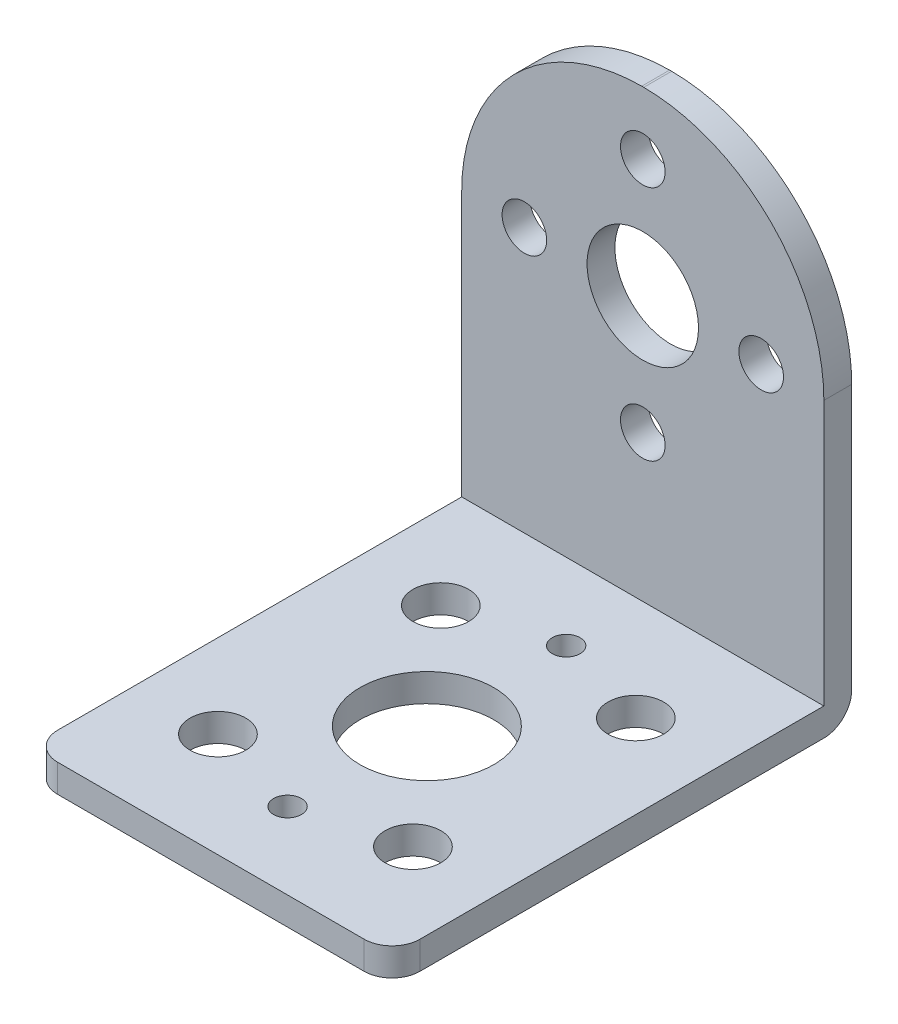
SolidWorks part; units mm, degrees
ref_plane "Front Plane" through (0, 0, 0) normal (0, 0, 1) x (1, 0, 0)
ref_plane "Top Plane" through (0, 0, 0) normal (0, 1, 0) x (1, 0, 0)
ref_plane "Right Plane" through (0, 0, 0) normal (1, 0, 0) x (0, 0, -1)
ref_plane "Plane1"
sketch "Sketch1" plane through (0, 0, 0) normal (0, 1, 0) x (-1, 0, 0)
  line L0 (-13, -15.5) -> (13, -15.5)
  line L1 (13, -15.5) -> (13, 15.5)
  line L2 (13, 15.5) -> (-13, 15.5)
  line L3 (-13, 15.5) -> (-13, -15.5)
  circle A0 centre (0, -10) radius 1
  circle A1 centre (0, 10) radius 1
  circle A2 centre (-7, 8) radius 2
  circle A3 centre (-7, -8) radius 2
  circle A4 centre (7, -8) radius 2
  circle A5 centre (7, 8) radius 2
  circle A6 centre (0, 0) radius 4.8
  dimension "D3" = 9.6
  dimension "D7" = 4
  dimension "D8" = 2
  dimension "D1" = 26
  dimension "D2" = 31
  dimension "D4" = 7.5
  dimension "D5" = 14
  dimension "D6" = 16
  dimension "D9" = 10
extrude "Extrusion1" add sketch "Sketch1" along normal blind 2 contours L2 L3 L0 L1 A6 A5 A4 A3 A2 A1 A0
ref_plane "Plane2"
sketch "Sketch2" plane through (0, 0, 0) normal (0, 1, 0) x (-1, 0, 0)
  line L0 (-13, -17.5) -> (13, -17.5)
  line L1 (13, -17.5) -> (13, -15.5)
  line L2 (13, -15.5) -> (-13, -15.5)
  line L3 (-13, -15.5) -> (-13, -17.5)
  dimension "D1" = 26
  dimension "D2" = 40.4599
  dimension "D3" = 2
  dimension "D4" = 26
extrude "Extrusion2" add sketch "Sketch2" along normal blind 34
sketch "Sketch3" plane through (0, 0, -15.5) normal (0, 0, 1) x (1, 0, 0)
  line L0 (-0.0721, 34) -> (-13, 34)
  line L1 (-13, 34) -> (-13, 21)
  line L2 (13, 21) -> (13, 34)
  line L3 (13, 34) -> (0.0721, 34)
  arc A0 (-0.0721, 33.9998) -> (-13, 21) centre (0, 21) ccw
  arc A1 (13, 21) -> (0.0721, 33.9998) centre (0, 21) ccw
  circle A2 centre (0, 29.5) radius 1.6
  circle A3 centre (8.5, 21) radius 1.6
  circle A4 centre (0, 12.5) radius 1.6
  circle A5 centre (-8.5, 21) radius 1.6
  circle A6 centre (0, 21) radius 4
  arc A7 (-0.0721, 34) -> (-0.0721, 33.9998) centre (-0.0721, 33.9999) cw
  arc A8 (0.0721, 34) -> (0.0721, 33.9998) centre (0.0721, 33.9999) ccw
  point P20 (0, 34)
  dimension "D1" = 8
  dimension "D4" = 3.2
  dimension "D5" = 0.0001
  dimension "D6" = 0.0001
  dimension "D2" = 13
  dimension "D3" = 8.5
extrude "Extrusion3" cut sketch "Sketch3" against normal blind 34
fillet "Fillet1" radius 2 1 edges at (0, 0, -17.5)
fillet "Fillet2" radius 2 2 edges at (-13, 1, 15.5) (13, 1, 15.5)
